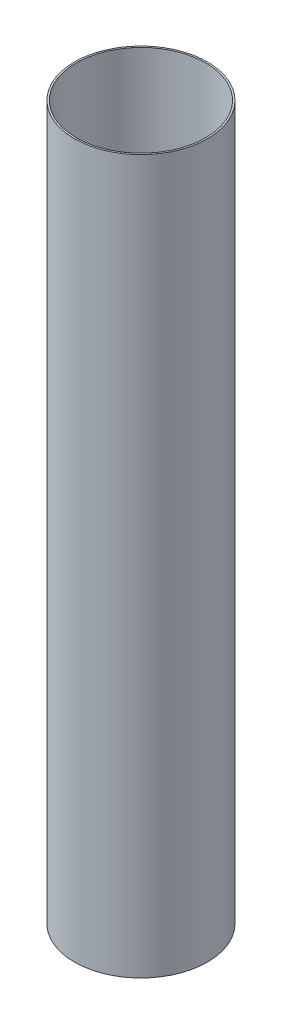
SolidWorks part; units mm, degrees
material "Thornel VCB-20 Carbon Cloth"
ref_plane "Front Plane" through (0, 0, 0) normal (0, 0, 1) x (1, 0, 0)
ref_plane "Top Plane" through (0, 0, 0) normal (0, 1, 0) x (1, 0, 0)
ref_plane "Right Plane" through (0, 0, 0) normal (1, 0, 0) x (0, 0, -1)
sketch "Sketch1" plane through (0, 0, 0) normal (0, 1, 0) x (1, 0, 0)
  circle A0 centre (0, 0) radius 25.4
  circle A1 centre (0, 0) radius 26.0604
  dimension "D1" = 50.8
  dimension "D2" = 0.6604
extrude "Boss-Extrude1" add sketch "Sketch1" along normal blind 279.4
